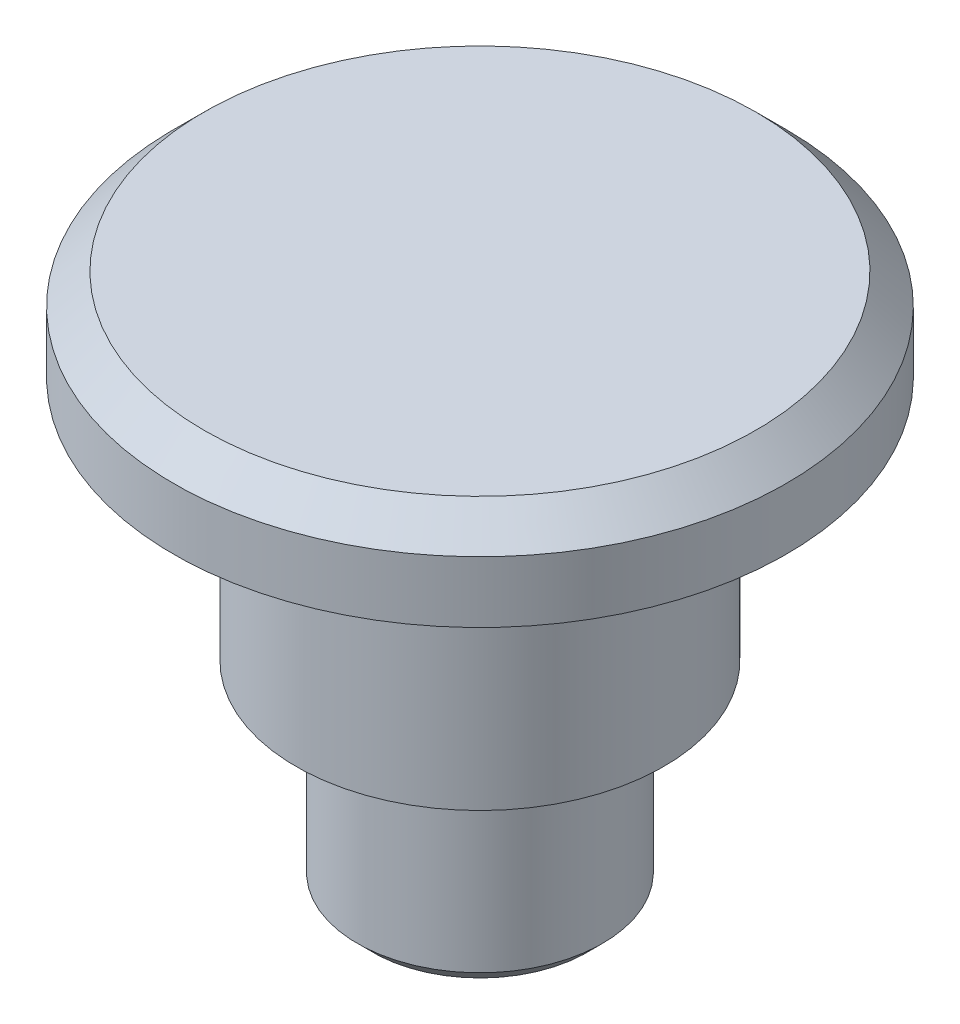
SolidWorks part; units mm, degrees
ref_plane "Plan1" through (0, 0, 0) normal (0, 0, 1) x (1, 0, 0)
ref_plane "Plan2" through (0, 0, 0) normal (0, 1, 0) x (1, 0, 0)
ref_plane "Plan3" through (0, 0, 0) normal (1, 0, 0) x (0, 0, -1)
sketch "Esquisse1" plane through (0, 0, 0) normal (0, 0, 1) x (1, 0, 0)
  line L0 (0, 0) -> (0, 100) construction
  line L1 (0, 0) -> (3.5, 0)
  line L2 (4, 0.5) -> (4, 6.5)
  line L3 (6, 6.5) -> (6, 14.5)
  line L4 (6.6, 14.5) -> (10, 14.5)
  line L5 (10, 16.5) -> (10, 14.5)
  line L7 (9, 17.5) -> (0, 17.5)
  line L8 (0, 17.5) -> (0, 0)
  line L9 (6, 6.5) -> (4.6, 6.5)
  line L10 (9, 17.5) -> (10, 16.5)
  line L11 (3.5, 0) -> (4, 0.5)
  arc A0 (4.6, 6.5) -> (4, 6.5) centre (4.3, 6.5) ccw
  arc A1 (6.6, 14.5) -> (6, 14.5) centre (6.3, 14.5) ccw
  point P3 (4, 0)
  dimension "D4" = 0.3
  dimension "D5" = 6
  dimension "D6" = 0.3
  dimension "D1" = 6.5
  dimension "D2" = 8
  dimension "D3" = 3
  dimension "D7" = 4
  dimension "D8" = 10
  dimension "D12" = 0.5
  dimension "D9" = 135
  dimension "D10" = 2
revolve "Base-Révolution" add sketch "Esquisse1" angle 360 about L0
